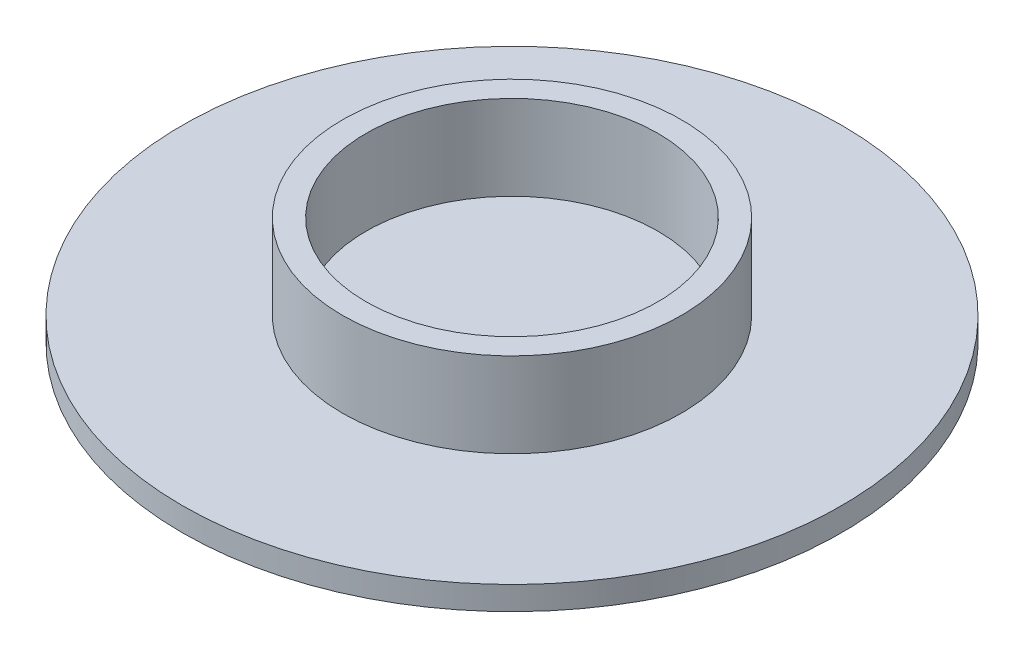
SolidWorks part; units mm, degrees
ref_plane "Front Plane" through (0, 0, 0) normal (0, 0, 1) x (1, 0, 0)
ref_plane "Top Plane" through (0, 0, 0) normal (0, 1, 0) x (1, 0, 0)
ref_plane "Right Plane" through (0, 0, 0) normal (1, 0, 0) x (0, 0, -1)
sketch "Sketch1" plane through (0, 0, 0) normal (1, 0, 0) x (0, 0, -1)
  line L0 (0, 0) -> (70, 0)
  line L1 (70, 0) -> (70, 5)
  line L2 (70, 5) -> (36, 5)
  line L3 (36, 5) -> (36, 23)
  line L4 (36, 23) -> (31, 23)
  line L5 (31, 23) -> (31, 5)
  line L6 (31, 5) -> (0, 5)
  line L7 (0, 5) -> (0, 0)
  dimension "D1" = 5
  dimension "D2" = 36
  dimension "D3" = 70
  dimension "D4" = 5
  dimension "D5" = 18
revolve "Revolve1" add sketch "Sketch1" angle 360 about L7
sketch "Sketch2" plane through (0, 0, 0) normal (0, -1, 0) x (1, 0, 0)
  circle A0 centre (0, 0) radius 60 construction
  circle A1 centre (0, 0) radius 70 construction
  point P5 (0, 41)
  point P14 (35.507, 20.5)
  point P15 (35.507, -20.5)
  point P16 (0, -41)
  point P17 (-35.507, -20.5)
  point P18 (-35.507, 20.5)
  dimension "D1" = 10
  dimension "D2" = 6
